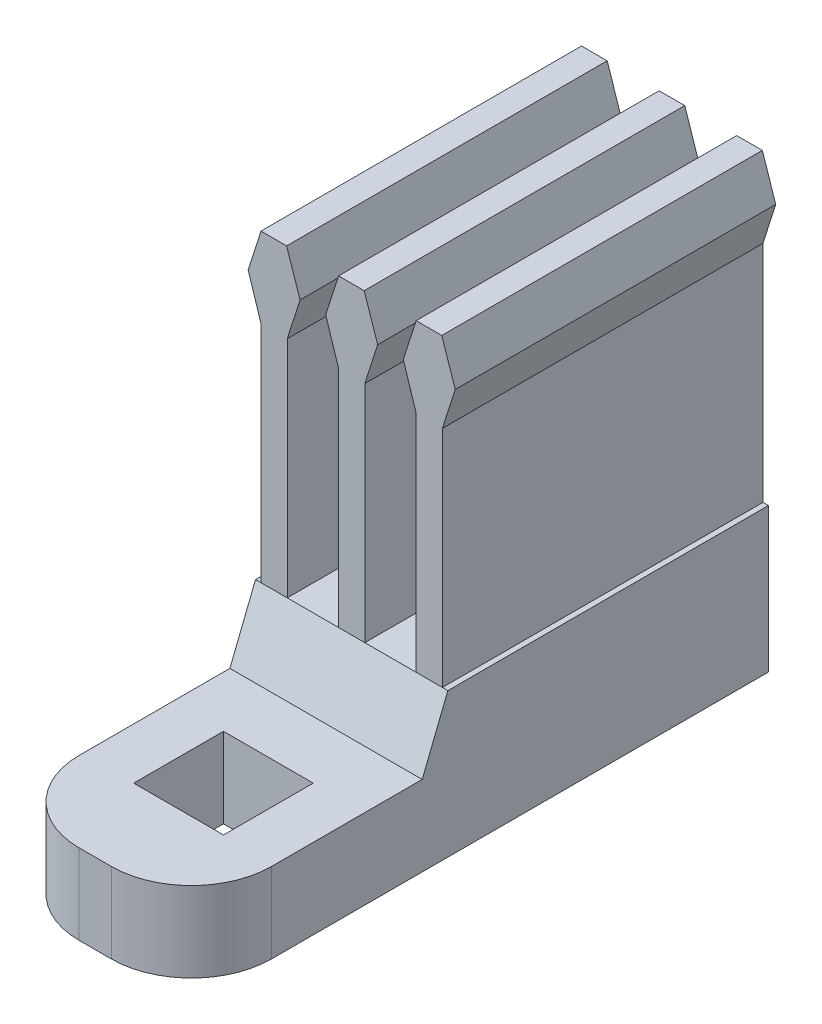
SolidWorks part; units mm, degrees
ref_plane "Plano frontal" through (0, 0, 0) normal (0, 0, 1) x (1, 0, 0)
ref_plane "Plano superior" through (0, 0, 0) normal (0, 1, 0) x (1, 0, 0)
ref_plane "Plano direito" through (0, 0, 0) normal (1, 0, 0) x (0, 0, -1)
sketch "Esboço1" plane through (0, 0, 0) normal (0, 0, 1) x (1, 0, 0)
  line L0 (-0.4, 0) -> (-0.57, 0)
  line L1 (0, 0) -> (0, 7) construction
  line L2 (0, 0) -> (0, 7) construction
  line L4 (-0.4, 7) -> (-0.4, 0)
  line L5 (0.42, 7) -> (0.42, 0)
  line L6 (0.42, 0) -> (2.02, 0)
  line L7 (2.02, 7) -> (2.02, 0)
  line L8 (-0.57, -2.5) -> (5.43, -2.5)
  line L14 (2.84, 7) -> (2.84, 0)
  line L15 (2.84, 0) -> (4.44, 0)
  line L16 (2.84, 7) -> (3.24, 8.25)
  line L17 (2.02, 9.5) -> (2.82, 9.5)
  line L18 (2.82, 9.5) -> (3.24, 8.25)
  line L19 (2.02, 7) -> (1.62, 8.25)
  line L20 (2.02, 9.5) -> (1.62, 8.25)
  line L21 (2.43, 0) -> (2.43, 7) construction
  line L22 (2.43, 7) -> (2.84, 7) construction
  line L23 (2.43, 7) -> (2.02, 7) construction
  line L24 (5.43, -2.5) -> (5.43, 0)
  line L25 (-0.57, -2.5) -> (-0.57, 0)
  line L26 (0, 7) -> (0.42, 7) construction
  line L27 (0, 7) -> (-0.4, 7) construction
  line L28 (0.42, 7) -> (0.82, 8.25)
  line L29 (-0.4, 9.5) -> (0.4, 9.5)
  line L30 (0.4, 9.5) -> (0.82, 8.25)
  line L31 (-0.4, 7) -> (-0.8, 8.25)
  line L32 (-0.4, 9.5) -> (-0.8, 8.25)
  line L34 (4.44, 7) -> (4.44, 0)
  line L35 (5.26, 7) -> (5.26, 0)
  line L36 (5.26, 0) -> (5.43, 0)
  line L37 (5.26, 7) -> (5.66, 8.25)
  line L38 (4.44, 9.5) -> (5.24, 9.5)
  line L39 (5.24, 9.5) -> (5.66, 8.25)
  line L42 (4.44, 7) -> (4.04, 8.25)
  line L43 (4.44, 9.5) -> (4.04, 8.25)
  line L44 (4.84, 0) -> (4.84, 7) construction
  line L45 (4.84, 7) -> (5.26, 7) construction
  line L46 (4.84, 7) -> (4.44, 7) construction
  point P4 (2, 12)
  point P32 (2.43, -2.5)
  dimension "D4" = 3
  dimension "D5" = 0.82
  dimension "D6" = 0.82
  dimension "D7" = 1.6
  dimension "D8" = 1.6
  dimension "D9" = 0.82
extrude "Ressalto-extrusão1" add sketch "Esboço1" along normal blind 10 contours L38 L43 L42 L34 L15 L14 L16 L18 L17 L20 L19 L7 L6 L5 L28 L30 L29 L32 L31 L4 L0 L25 L8 L24 L36 L35 L37 L39
sketch "Esboço2" plane through (0, 0, 10) normal (0, 0, 1) x (1, 0, 0)
  line L1 (-0.57, -2.5) -> (5.43, -2.5)
  line L2 (-0.57, -2.5) -> (-0.57, 0)
  line L3 (-0.57, 0) -> (5.43, 0)
  line L4 (5.43, -2.5) -> (5.43, 0)
extrude "Ressalto-extrusão2" add sketch "Esboço2" along normal blind 8
sketch "Esboço3" plane through (0, -2.5, 0) normal (0, -1, 0) x (1, 0, 0)
  line L0 (2.43, 18) -> (2.43, 14) construction
  line L1 (-0.57, 18) -> (5.43, 18) construction
  line L3 (1.03, 15.4) -> (3.83, 15.4)
  line L4 (1.03, 15.4) -> (1.03, 12.6)
  line L5 (1.03, 12.6) -> (3.83, 12.6)
  line L6 (3.83, 15.4) -> (3.83, 12.6)
  line L7 (1.03, 15.4) -> (3.83, 12.6) construction
  line L8 (1.03, 12.6) -> (3.83, 15.4) construction
  dimension "D1" = 2.8
extrude "Corte-extrusão1" cut sketch "Esboço3" against normal through all
sketch "Esboço4" plane through (0, -2.5, 0) normal (0, -1, 0) x (1, 0, 0)
  line L0 (3.83, 12.6) -> (3.83, 15.4) construction
  line L1 (1.03, 12.6) -> (3.83, 12.6) construction
  line L2 (1.03, 15.4) -> (1.03, 12.6) construction
  line L3 (3.83, 15.4) -> (1.03, 15.4) construction
  line L4 (-0.57, 0) -> (5.43, 0)
  line L5 (5.43, 0) -> (5.43, 18)
  line L6 (5.43, 18) -> (-0.57, 18)
  line L7 (-0.57, 18) -> (-0.57, 0)
  line L8 (-0.57, 0) -> (5.43, 0)
  line L9 (5.43, 0) -> (5.43, 18)
  line L10 (5.43, 18) -> (-0.57, 18)
  line L11 (-0.57, 18) -> (-0.57, 0)
  line L12 (3.83, 12.6) -> (3.83, 15.4)
  line L13 (1.03, 12.6) -> (3.83, 12.6)
  line L14 (1.03, 15.4) -> (1.03, 12.6)
  line L15 (3.83, 15.4) -> (1.03, 15.4)
  dimension "D1" = 0
extrude "Ressalto-extrusão3" add sketch "Esboço4" along normal blind 2
sketch "Esboço6" plane through (0, 0, 0) normal (1, 0, 0) x (0, 0, -1)
  line L0 (-18, 0) -> (-18, -2)
  line L1 (-18, -4.5) -> (-18, 0) construction
  line L2 (-18, -2) -> (-14, -2) construction
  line L3 (-14, -2) -> (-10.8, -2)
  line L4 (-10.8, -2) -> (-10, 0)
  line L5 (-10, 0) -> (-18, 0)
  line L6 (-18, -2) -> (-14, -2)
  dimension "D1" = 2
extrude "Corte-extrusão3" cut sketch "Esboço6" against normal through all and the other way through all
sketch "Esboço7" plane through (0, -2, 0) normal (0, 1, 0) x (1, 0, 0)
  line L0 (-0.57, -15.5) -> (-3.3213, -15.5)
  line L1 (-3.3213, -15.5) -> (-3.3213, -18.8576)
  line L2 (-3.3213, -18.8576) -> (8.5469, -18.8576)
  line L3 (8.5469, -18.8576) -> (8.5469, -15.5)
  line L4 (-0.57, -10.8) -> (-0.57, -18)
  line L5 (-0.57, -18) -> (5.43, -18)
  line L6 (5.43, -18) -> (5.43, -10.8)
  line L7 (5.43, -10.8) -> (-0.57, -10.8)
  line L9 (1.93, -18) -> (2.93, -18)
  line L12 (8.5469, -15.5) -> (5.43, -15.5)
  arc A0 (2.93, -18) -> (5.43, -15.5) centre (2.93, -15.5) ccw
  arc A1 (-0.57, -15.5) -> (1.93, -18) centre (1.93, -15.5) ccw
  dimension "D2" = 2.5
  dimension "D1" = 0
extrude "Corte-extrusão4" cut sketch "Esboço7" against normal through all
